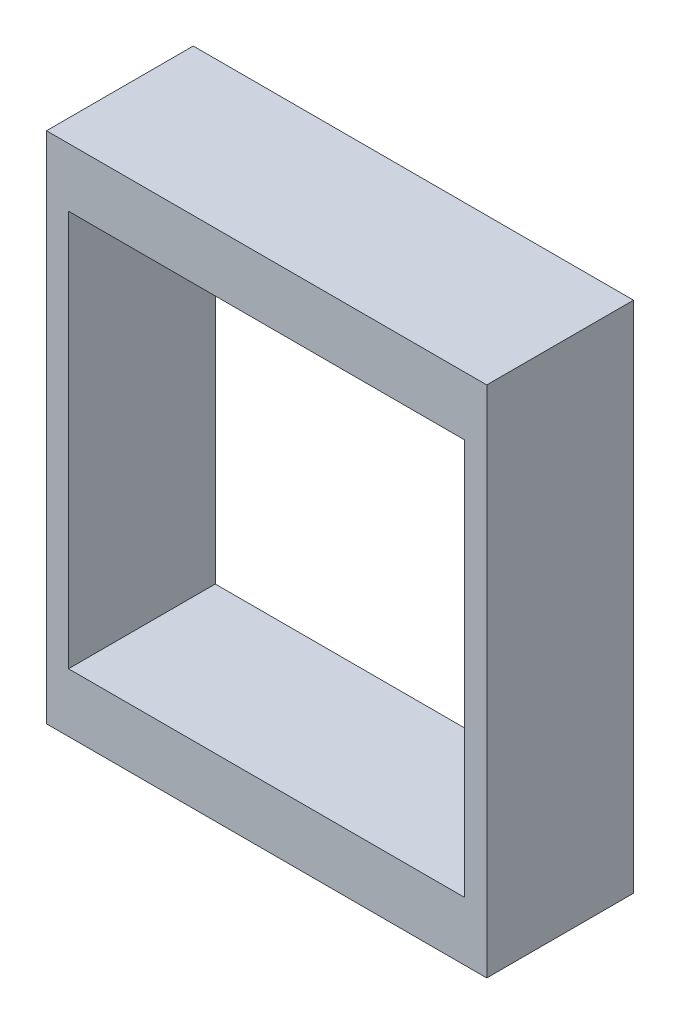
SolidWorks part; units mm, degrees
ref_plane "前视基准面" through (0, 0, 0) normal (0, 0, 1) x (1, 0, 0)
ref_plane "上视基准面" through (0, 0, 0) normal (0, 1, 0) x (1, 0, 0)
ref_plane "右视基准面" through (0, 0, 0) normal (1, 0, 0) x (0, 0, -1)
other "Configuration Table"
sketch "草图1" plane through (0, 0, 0) normal (0, 0, 1) x (1, 0, 0)
  line L1 (-60, 70) -> (60, 70)
  line L2 (-60, 70) -> (-60, -70)
  line L3 (-60, -70) -> (60, -70)
  line L4 (60, 70) -> (60, -70)
  line L5 (-60, 70) -> (60, -70) construction
  line L6 (-60, -70) -> (60, 70) construction
  line L7 (-54, 54) -> (54, 54)
  line L8 (-54, 54) -> (-54, -54)
  line L9 (-54, -54) -> (54, -54)
  line L10 (54, 54) -> (54, -54)
  line L11 (-54, 54) -> (54, -54) construction
  line L12 (-54, -54) -> (54, 54) construction
  point P0 (0, 0)
  point P5 (0, 0)
  dimension "D1" = 140
  dimension "D2" = 120
  dimension "D3" = 6
extrude "凸台-拉伸1" add sketch "草图1" along normal mid plane 40
